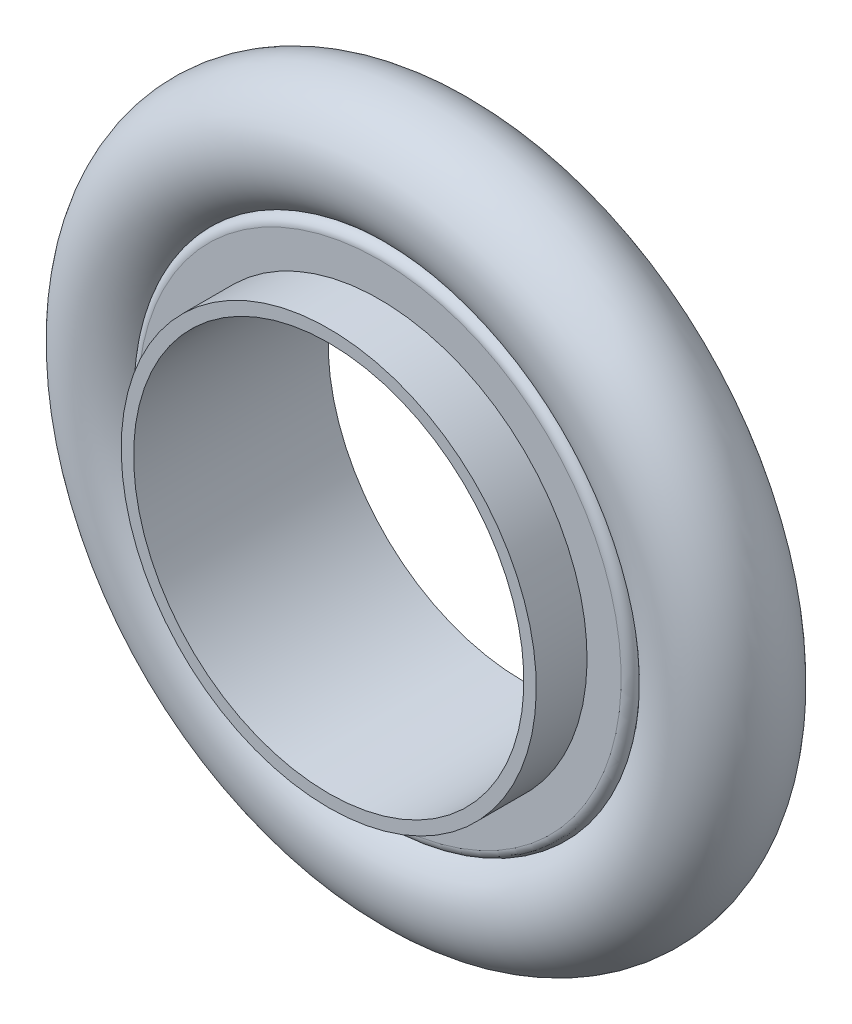
SolidWorks part; units mm, degrees
ref_plane "Front Plane" through (0, 0, 0) normal (0, 0, 1) x (1, 0, 0)
ref_plane "Top Plane" through (0, 0, 0) normal (0, 1, 0) x (1, 0, 0)
ref_plane "Right Plane" through (0, 0, 0) normal (1, 0, 0) x (0, 0, -1)
sketch "Sketch1" plane through (0, 0, 0) normal (1, 0, 0) x (0, 0, -1)
  line L0 (0, 0) -> (0, 12.1613) construction
  line L1 (-3.9878, 0) -> (3.9878, 0) construction
  line L2 (-3.9878, 8.001) -> (3.9878, 8.001) construction
  line L3 (-3.9878, 8.001) -> (-3.9878, 8.509) construction
  line L4 (-3.9878, 8.509) -> (-1.905, 8.509) construction
  line L5 (-1.905, 8.509) -> (-1.905, 9.906) construction
  line L6 (-1.524, 10.287) -> (1.524, 10.287) construction
  line L7 (1.905, 8.509) -> (1.905, 9.906) construction
  line L8 (3.9878, 8.509) -> (1.905, 8.509) construction
  line L9 (3.9878, 8.001) -> (3.9878, 8.509) construction
  line L10 (-3.9878, 14.986) -> (-3.9878, -14.986) construction
  line L11 (3.9878, 8.001) -> (3.9878, -8.001) construction
  line L12 (-3.9878, -8.636) -> (-3.9878, 8.636)
  circle A0 centre (0, 12.1613) radius 2.4157 construction
  arc A1 (-1.905, 9.906) -> (-1.524, 10.287) centre (-1.524, 9.906) cw construction
  arc A2 (1.905, 9.906) -> (1.524, 10.287) centre (1.524, 9.906) ccw construction
  point P7 (0, 0)
  point P10 (0, 8.001)
  point P23 (-3.9878, 0)
  point P26 (3.9878, 0)
  point P31 (-3.9878, 0)
  dimension "D3" = 0.381
  dimension "Ring OD" = 29.1541
  dimension "Length" = 7.9756
  dimension "For Tube OD" = 17.272
  dimension "D2" = 2.286
  dimension "D4" = 3.81
  dimension "For Flange OD" = 29.972
  dimension "Wall Thichness" = 0.508
  dimension "ID" = 16.002
sketch "Sketch4" plane through (0, 0, 0) normal (0, 0, 1) x (1, 0, 0)
  circle A0 centre (0, 0) radius 14.986 construction
  circle A1 centre (0, 0) radius 8.636 construction
sketch "Sketch2" plane through (0, 0, 0) normal (1, 0, 0) x (0, 0, -1)
  line L0 (-1.905, 8.509) -> (-1.905, 9.906) construction
  line L1 (-1.905, 8.509) -> (-1.905, 9.906)
  line L2 (-3.9878, 8.509) -> (-1.905, 8.509) construction
  line L3 (-3.9878, 8.509) -> (-1.905, 8.509)
  line L4 (-3.9878, 8.001) -> (-3.9878, 8.509) construction
  line L5 (-3.9878, 8.001) -> (-3.9878, 8.509)
  line L6 (-3.9878, 8.001) -> (3.9878, 8.001) construction
  line L7 (-3.9878, 8.001) -> (3.9878, 8.001)
  line L8 (3.9878, 8.001) -> (3.9878, 8.509) construction
  line L9 (3.9878, 8.001) -> (3.9878, 8.509)
  line L10 (3.9878, 8.509) -> (1.905, 8.509) construction
  line L11 (3.9878, 8.509) -> (1.905, 8.509)
  line L12 (1.905, 8.509) -> (1.905, 9.906) construction
  line L13 (1.905, 8.509) -> (1.905, 9.906)
  arc A2 (-1.524, 10.287) -> (-1.905, 9.906) centre (-1.524, 9.906) ccw construction
  arc A3 (-1.524, 10.287) -> (-1.905, 9.906) centre (-1.524, 9.906) ccw
  arc A4 (1.905, 9.906) -> (1.524, 10.287) centre (1.524, 9.906) ccw construction
  arc A5 (1.905, 9.906) -> (1.524, 10.287) centre (1.524, 9.906) ccw
  circle A6 centre (0, 12.1613) radius 2.4157 construction
  arc A7 (-1.524, 10.287) -> (1.524, 10.287) centre (0, 12.1613) ccw
revolve "Revolve1" add sketch "Sketch2" angle 360 about L1
sketch "Sketch3" plane through (0, 0, 0) normal (1, 0, 0) x (0, 0, -1)
  circle A0 centre (0, 12.1613) radius 2.4157 construction
  circle A1 centre (0, 12.1613) radius 2.4157
revolve "Revolve2" add sketch "Sketch3" angle 360 about L1
